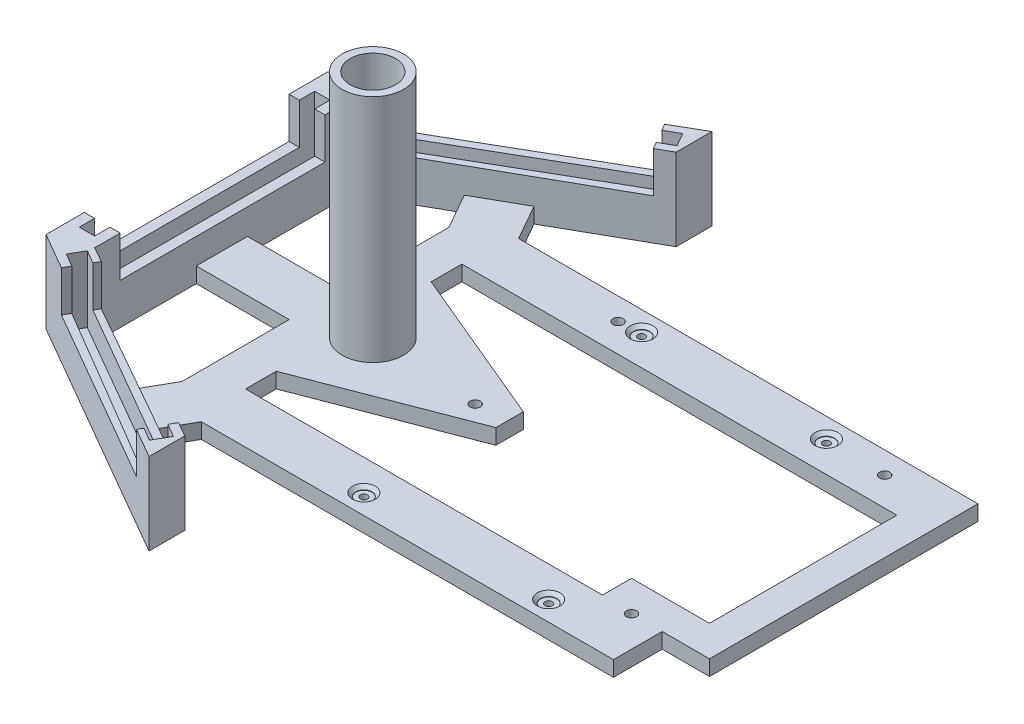
SolidWorks part; units mm, degrees
ref_plane "Front Plane" through (0, 0, 0) normal (0, 0, 1) x (1, 0, 0)
ref_plane "Top Plane" through (0, 0, 0) normal (0, 1, 0) x (1, 0, 0)
ref_plane "Right Plane" through (0, 0, 0) normal (1, 0, 0) x (0, 0, -1)
sketch "Sketch1" plane through (0, 0, 0) normal (0, 1, 0) x (1, 0, 0)
  line L0 (-76.3736, 27.5) -> (-76.3736, -27.5)
  line L1 (-76.3736, -27.5) -> (-28.7422, -55)
  line L2 (-76.3736, 27.5) -> (-28.7422, 55)
  line L3 (-28.7422, 55) -> (-28.7422, 31)
  line L4 (-28.7422, 31) -> (47.2578, 31)
  line L5 (47.2578, 31) -> (47.2578, -31)
  line L6 (47.2578, -31) -> (-28.7422, -31)
  line L7 (-28.7422, -31) -> (-28.7422, -55)
  line L8 (-28.7422, 31) -> (-28.7422, -31) construction
  point P2 (-28.7422, 0)
  point P3 (-76.3736, 0)
  dimension "D1" = 55
  dimension "D2" = 55
  dimension "D3" = 55
  dimension "D4" = 76
  dimension "D5" = 62
  dimension "D6" = 120
  dimension "D7" = 120
  dimension "D8" = 62.0573
extrude "Boss-Extrude1" add sketch "Sketch1" along normal blind 3 contours L1 L7 L6 L5 L4 L3 L2 L0
sketch "Sketch2" plane through (0, 0, 0) normal (0, 1, 0) x (1, 0, 0)
  line L0 (-76.3736, 27.5) -> (-76.3736, -27.5) construction
  line L1 (-76.3736, 27.5) -> (-28.7422, 55) construction
  line L2 (-52.5579, 41.25) -> (-41.6795, 22.408) construction
  line L3 (-76.3736, -27.5) -> (-28.7422, -55) construction
  line L4 (-52.5579, -41.25) -> (-39.7277, -19.0274) construction
  circle A1 centre (-51.0579, 38.6519) radius 1.5
  circle A2 centre (-73.3736, 0) radius 1.5
  circle A3 centre (-51.0579, -38.6519) radius 1.5
  point P8 (-76.3736, 0)
  dimension "D1" = 3
  dimension "D2" = 3
  dimension "D3" = 3
  dimension "D4" = 3
sketch "Sketch4" plane through (0, 0, 0) normal (1, 0, 0) x (0, 0, -1)
  line L0 (-31, 3) -> (-31, 23)
  line L1 (-31, 23) -> (31, 23)
  line L2 (31, 23) -> (31, 3)
  line L3 (55, 3) -> (31, 3) construction
  line L4 (31, 3) -> (28, 3)
  line L5 (31, 3) -> (-31, 3) construction
  line L6 (28, 3) -> (28, 20)
  line L7 (28, 20) -> (-28, 20)
  line L8 (-28, 20) -> (-28, 3)
  line L9 (-28, 3) -> (-31, 3)
  dimension "D1" = 20
  dimension "D2" = 62
  dimension "D3" = 3
  dimension "D4" = 3
ref_plane "Plane1" through (-81, 0, 0) normal (1, 0, 0) x (0, 0, -1)
sketch "Sketch11" plane through (0, 3, 0) normal (0, 1, 0) x (1, 0, 0)
  line L0 (-28.7422, -55) -> (-28.7422, -48)
  line L1 (-28.7422, -31) -> (-28.7422, -55) construction
  line L2 (-28.7422, -48) -> (-69.3736, -24.9795)
  line L3 (-69.3736, -24.9795) -> (-69.3736, 24.9795)
  line L4 (-69.3736, 24.9795) -> (-28.7422, 48)
  line L5 (-76.3736, -27.5) -> (0, 0) construction
  line L6 (-28.7422, 48) -> (-28.7422, 55)
  line L7 (-28.7422, 55) -> (-76.3736, 27.5)
  line L8 (-76.3736, 27.5) -> (-76.3736, -27.5)
  line L9 (-76.3736, -27.5) -> (-28.7422, -55)
  line L10 (0, 0) -> (-76.3736, 27.5) construction
  line L11 (-76.3736, -27.5) -> (-28.7422, -55) construction
  line L12 (-28.7422, 55) -> (-28.7422, 31) construction
  line L13 (-76.3736, 27.5) -> (-28.7422, 55) construction
  dimension "D1" = 7
  dimension "D3" = 7
  dimension "D5" = 7
extrude "Boss-Extrude7" add sketch "Sketch11" along normal blind 13
sketch "Sketch14" plane through (0, 16, 0) normal (0, 1, 0) x (1, 0, 0)
  line L0 (-29.7422, 49.2103) -> (-69.5794, 26.2103)
  line L1 (-74.3736, 23) -> (-71.3736, 23)
  line L2 (-74.3736, 23) -> (-74.3736, -23)
  line L3 (-74.3736, -23) -> (-71.3736, -23)
  line L4 (-71.3736, 23) -> (-71.3736, -23)
  line L6 (-29.7422, 49.2103) -> (-31.2422, 51.8084)
  line L7 (-69.5794, 26.2103) -> (-71.0794, 28.8084)
  line L8 (-31.2422, 51.8084) -> (-71.0794, 28.8084)
  line L9 (-71.0794, -28.8084) -> (-31.477, -52.2103)
  line L10 (-71.0794, -28.8084) -> (-69.5794, -26.2103)
  line L11 (-28.7422, 48) -> (-28.7422, 55) construction
  line L12 (-31.477, -52.2103) -> (-29.7422, -49.2103)
  line L13 (-28.7422, 48) -> (-28.7422, 31) construction
  line L17 (-69.5794, -26.2103) -> (-29.7422, -49.2103)
  line L18 (-28.7422, -55) -> (-28.7422, -48) construction
  line L19 (-28.7422, -31) -> (-28.7422, -48) construction
  dimension "D1" = 46
  dimension "D2" = 3
  dimension "D3" = 3
  dimension "D4" = 46
  dimension "D5" = 46
  dimension "D6" = 1
  dimension "D7" = 3
  dimension "D8" = 1
  dimension "D9" = 3
  dimension "D10" = 60
  dimension "D11" = 60
  dimension "D12" = 46
  dimension "D13" = 60
  dimension "D14" = 57.5
  dimension "D15" = 57.5
  dimension "D16" = 3.6777
  dimension "D17" = 3.6777
extrude "Cut-Extrude1" cut sketch "Sketch14" against normal blind 13
sketch "Sketch15" plane through (0, 16, 0) normal (0, 1, 0) x (1, 0, 0)
  line L0 (-76.3736, 20) -> (-69.3736, 20)
  line L1 (-76.3736, 27.5) -> (-76.3736, -27.5) construction
  line L2 (-69.3736, -24.9795) -> (-69.3736, 24.9795) construction
  line L3 (-69.3736, 20) -> (-69.3736, -20)
  line L4 (-69.3736, -20) -> (-76.3736, -20)
  line L5 (-76.3736, -20) -> (-76.3736, 20)
  line L6 (-69.2383, 31.6196) -> (-66.4233, 26.651)
  line L7 (-28.7422, 55) -> (-76.3736, 27.5) construction
  line L8 (-69.3736, 24.9795) -> (-28.7422, 48) construction
  line L9 (-66.4233, 26.651) -> (-31.5794, 46.3925)
  line L10 (-69.3736, 24.9795) -> (-28.7422, 48) construction
  line L11 (-31.5794, 46.3925) -> (-34.5973, 51.6196)
  line L12 (-34.5973, 51.6196) -> (-69.2383, 31.6196)
  line L13 (-66.396, -26.6665) -> (-69.2513, -31.612)
  line L14 (-28.7422, -48) -> (-69.3736, -24.9795) construction
  line L15 (-76.3736, -27.5) -> (-28.7422, -55) construction
  line L16 (-69.2513, -31.612) -> (-34.569, -51.6359)
  line L17 (-34.569, -51.6359) -> (-31.5937, -46.3844)
  line L18 (-28.7422, -48) -> (-69.3736, -24.9795) construction
  line L19 (-31.5937, -46.3844) -> (-66.396, -26.6665)
  line L20 (-74.3736, 23) -> (-74.3736, -23) construction
  line L21 (-31.477, -52.2103) -> (-29.7422, -49.2103) construction
  line L22 (-74.3736, -23) -> (-71.3736, -23) construction
  line L23 (-29.7422, 49.2103) -> (-31.2422, 51.8084) construction
  line L24 (-71.3736, 23) -> (-74.3736, 23) construction
  point P24 (-33.0813, -49.0102)
  point P31 (-30.6096, -50.7103)
  point P34 (-72.8736, -20)
  dimension "D1" = 40
  dimension "D2" = 40
  dimension "D3" = 40
  dimension "D4" = 3
  dimension "D5" = 3
  dimension "D6" = 3
  dimension "D7" = 5.7106
  dimension "D8" = 5.7106
extrude "Cut-Extrude3" cut sketch "Sketch15" against normal blind 8
sketch "Sketch17" plane through (0, 3, 0) normal (0, 1, 0) x (1, 0, 0)
  line L0 (-69.3736, -24.9795) -> (-69.3736, -5.1309)
  line L1 (-69.3736, -5.1309) -> (-51.2191, -5.1309)
  line L2 (-51.2191, -5.1309) -> (-51.2191, -26.0705)
  line L3 (-51.2191, -26.0705) -> (-55.1626, -33.031)
  line L4 (-55.1626, -33.031) -> (-69.3736, -24.9795)
  line L5 (-69.3736, 24.9795) -> (-69.3736, 4.8691)
  line L6 (-69.3736, 4.8691) -> (-51.2191, 4.8691)
  line L7 (-51.2191, 4.8691) -> (-51.2191, 26.0705)
  line L8 (-51.2191, 26.0705) -> (-55.1626, 33.031)
  line L10 (-28.7422, -48) -> (-46.4621, -37.9605)
  line L11 (-46.4621, -37.9605) -> (-42.5185, -31)
  line L12 (-42.5185, -31) -> (-28.7422, -31)
  line L13 (-28.7422, -31) -> (-28.7422, -48)
  line L14 (-28.7422, 31) -> (-42.5185, 31)
  line L15 (-42.5185, 31) -> (-46.4621, 37.9605)
  line L16 (-46.4621, 37.9605) -> (-28.7422, 48)
  line L17 (-28.7422, 48) -> (-28.7422, 31)
  line L19 (-31.5794, 46.3925) -> (-28.7422, 48) construction
  line L20 (-66.396, -26.6665) -> (-69.3736, -24.9795) construction
  line L21 (-28.7422, -48) -> (-31.5937, -46.3844) construction
  line L22 (-69.3736, 24.9795) -> (-55.1626, 33.031)
  line L23 (-69.3736, 24.9795) -> (-28.7422, 48) construction
  line L25 (47.2578, -31) -> (-28.7422, -31) construction
  dimension "D1" = 8
  dimension "D2" = 8
  dimension "D3" = 8
  dimension "D4" = 8
  dimension "D5" = 10
  dimension "D6" = 10
  dimension "D7" = 90
  dimension "D8" = 90
  dimension "D9" = 10
  dimension "D10" = 25.8691
extrude "Cut-Extrude5" cut sketch "Sketch17" against normal up to next
sketch "Sketch18" plane through (0, 3, 0) normal (0, 1, 0) x (1, 0, 0)
  circle A0 centre (-40, 0) radius 4.445
  circle A1 centre (-40, 0) radius 6
  dimension "D1" = 8.89
  dimension "D2" = 12
  dimension "D3" = 40
extrude "Boss-Extrude8" add sketch "Sketch18" along normal blind 45
sketch "Sketch19" plane through (0, 3, 0) normal (0, 1, 0) x (1, 0, 0)
  line L0 (47.2578, -31) -> (-27.9422, -31) construction
  line L1 (47.2578, -31) -> (-42.5185, -31) construction
  line L2 (-27.9422, -31) -> (-27.9422, 31) construction
  line L3 (-42.5185, 31) -> (47.2578, 31) construction
  line L4 (-27.9422, 31) -> (47.2578, 31) construction
  line L5 (47.2578, 31) -> (47.2578, -31) construction
  dimension "D1" = 75.2
hole_wizard "CBORE for #00 Binding Head Machine Screw1" positions "Sketch20" profile "Sketch21" counterbore size "#00" standard "ANSI Inch" end condition through all
sketch "Sketch20" plane through (0, 3, 0) normal (0, 1, 0) x (1, 0, 0)
  line L0 (47.2578, -31) -> (-42.5185, -31) construction
  line L1 (-42.5185, 31) -> (47.2578, 31) construction
  line L2 (47.2578, 31) -> (47.2578, -31) construction
  point P0 (-14.6222, -27.14)
  point P2 (-14.6222, 27.14)
  point P4 (21.4978, 27.14)
  point P6 (21.4978, -27.14)
  dimension "D1" = 3.86
  dimension "D2" = 3.86
  dimension "D3" = 3.86
  dimension "D4" = 3.86
  dimension "D5" = 25.76
  dimension "D6" = 25.76
  dimension "D7" = 36.12
  dimension "D8" = 36.12
sketch "Sketch21" plane through (-14.6222, 3, 27.14) normal (1, 0, 0) x (0, 0, 1)
  line L0 (0, 0) -> (0, 3)
  line L1 (0, 3) -> (0.6985, 3)
  line L3 (0.6985, 3) -> (0.6985, 0.7112)
  line L4 (1.5875, 0.7112) -> (0.6985, 0.7112)
  line L5 (1.5875, 0.7112) -> (1.5875, 0.635)
  line L6 (1.5875, 0.635) -> (2.2225, 0)
  line L7 (2.2225, 0) -> (0, 0)
  line L8 (-1.5875, 0.635) -> (-2.2225, 0) construction
  line L11 (0, -6.35) -> (0, 107.95) construction
  dimension "Thru Hole Dia." = 1.397
  dimension "Thru Hole Depth" = 3
  dimension "C'Bore Dia." = 3.175
  dimension "C'Bore Depth" = 0.7112
  dimension "Near C'Sink Dia." = 4.445
  dimension "Near C'Sink Angle" = 90
sketch "Sketch22" plane through (0, 3, 0) normal (0, 1, 0) x (1, 0, 0)
  line L0 (47.2578, 31) -> (47.2578, -31) construction
  line L2 (47.2578, -31) -> (47.2578, -26.67) construction
  line L5 (47.2578, -31) -> (-42.5185, -31) construction
  circle A0 centre (33.2878, 26.735) radius 1
  circle A1 centre (32.0178, -21.4703) radius 1
  circle A2 centre (-18.7422, 26.67) radius 1
  circle A3 centre (-18.7422, -1.26) radius 1
  dimension "D1" = 2
  dimension "D2" = 2
  dimension "D3" = 2
  dimension "D4" = 2
  dimension "D10" = 57.67
  dimension "D5" = 13.97
  dimension "D6" = 15.24
  dimension "D7" = 66
  dimension "D8" = 66
  dimension "D9" = 48.2053
  dimension "D13" = 9.5297
  dimension "D14" = 29.74
extrude "Cut-Extrude6" cut sketch "Sketch22" against normal through all
sketch "Sketch23" plane through (0, 3, 0) normal (0, 1, 0) x (1, 0, 0)
  line L0 (-43.7422, 21.14) -> (-43.7422, 15.14)
  line L1 (-43.7422, 15.14) -> (-12.7422, 2.14)
  line L2 (-12.7422, 2.14) -> (-12.7422, -3.207)
  line L3 (-12.7422, -3.207) -> (-43.7422, -15.14)
  line L4 (-43.7422, -15.14) -> (-43.7422, -21.14)
  line L5 (-43.7422, -21.14) -> (26.0178, -21.14)
  line L6 (26.0178, -21.14) -> (26.0178, -15.4703)
  line L7 (26.0178, -15.4703) -> (41.2578, -15.4703)
  line L8 (41.2578, -15.4703) -> (41.2578, 21.14)
  line L9 (41.2578, 21.14) -> (-43.7422, 21.14)
  line L10 (47.2578, 31) -> (47.2578, -31) construction
  line L11 (47.2578, -31) -> (-42.5185, -31) construction
  circle A0 centre (-14.6222, -27.14) radius 0.6985 construction
  circle A1 centre (-14.6222, 27.14) radius 0.6985 construction
  circle A2 centre (-18.7422, -1.26) radius 1 construction
  circle A3 centre (32.0178, -21.4703) radius 1 construction
  dimension "D1" = 6
  dimension "D2" = 6
  dimension "D5" = 6
  dimension "D6" = 6
  dimension "D3" = 6
  dimension "D4" = 6
  dimension "D9" = 6
  dimension "D10" = 85
  dimension "D11" = 27.793
  dimension "D12" = 33.14
extrude "Cut-Extrude8" cut sketch "Sketch23" against normal through all
sketch "Sketch24" plane through (0, 3, 0) normal (0, 1, 0) x (1, 0, 0)
  line L0 (26.0178, -15.4703) -> (41.2578, -15.4703) construction
  line L1 (38.0178, -21.4703) -> (47.2578, -21.4703)
  line L2 (38.0178, -21.4703) -> (38.0178, -31)
  line L3 (38.0178, -31) -> (47.2578, -31)
  line L4 (47.2578, -21.4703) -> (47.2578, -31)
  circle A0 centre (32.0178, -21.4703) radius 1 construction
  dimension "D1" = 6
  dimension "D2" = 6
extrude "Cut-Extrude9" cut sketch "Sketch24" against normal through all
